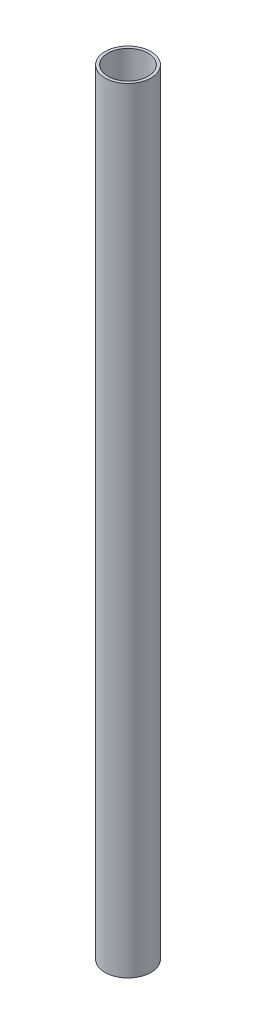
SolidWorks part; units mm, degrees
material "Hexcel AS4C (3000 丝)"
ref_plane "前视基准面" through (0, 0, 0) normal (0, 0, 1) x (1, 0, 0)
ref_plane "上视基准面" through (0, 0, 0) normal (0, 1, 0) x (1, 0, 0)
ref_plane "右视基准面" through (0, 0, 0) normal (1, 0, 0) x (0, 0, -1)
sketch "草图1" plane through (0, 0, 0) normal (0, 1, 0) x (1, 0, 0)
  circle A0 centre (0, 0) radius 8
  circle A1 centre (0, 0) radius 7
  dimension "D1" = 16
  dimension "D2" = 14
extrude "凸台-拉伸1" add sketch "草图1" along normal blind 270
